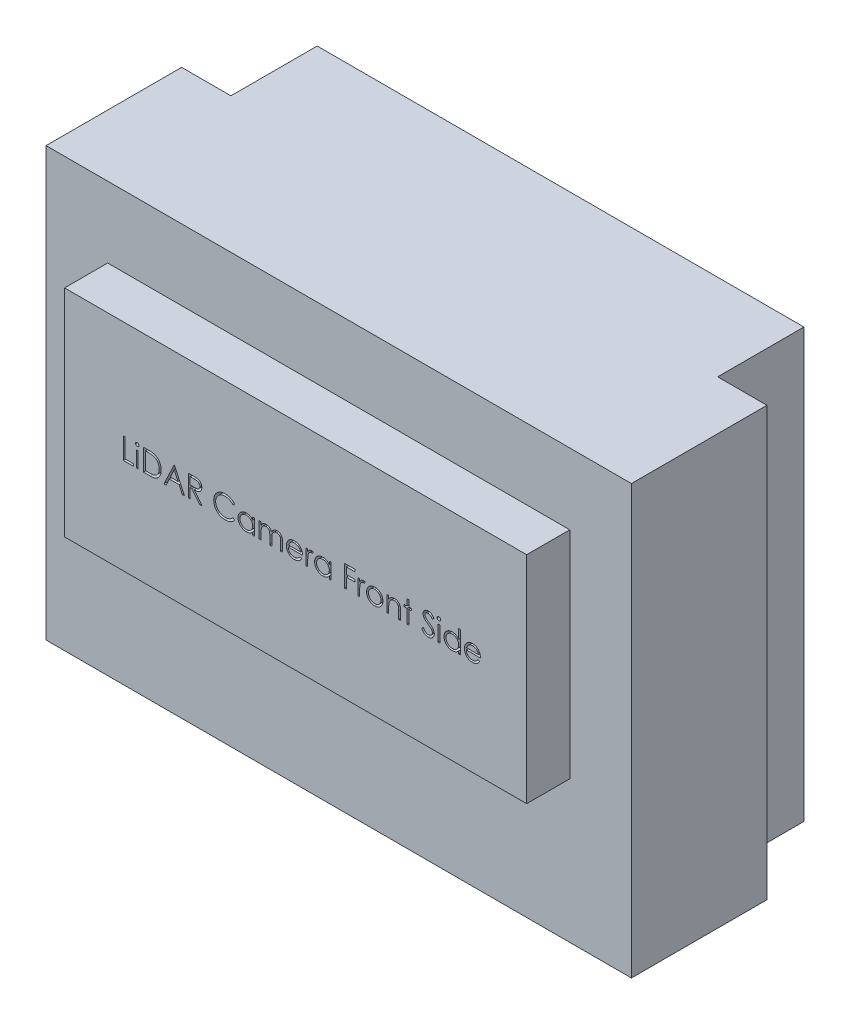
SolidWorks part; units mm, degrees
ref_plane "Front Plane" through (0, 0, 0) normal (0, 0, 1) x (1, 0, 0)
ref_plane "Top Plane" through (0, 0, 0) normal (0, 1, 0) x (1, 0, 0)
ref_plane "Right Plane" through (0, 0, 0) normal (1, 0, 0) x (0, 0, -1)
sketch "Sketch1" plane through (0, 0, 0) normal (0, 0, 1) x (1, 0, 0)
  line L1 (0, 0) -> (95, 0)
  line L2 (0, 0) -> (0, 69.5)
  line L3 (0, 69.5) -> (95, 69.5)
  line L4 (95, 0) -> (95, 69.5)
  dimension "D1" = 95
  dimension "D2" = 69.5
extrude "Body" add sketch "Sketch1" along normal blind 22
sketch "Sketch2" plane through (0, 0, 22) normal (0, 0, 1) x (1, 0, 0)
  line L1 (10, 58) -> (85, 58)
  line L2 (10, 58) -> (10, 23)
  line L3 (10, 23) -> (85, 23)
  line L4 (85, 58) -> (85, 23)
  line L5 (0, 69.5) -> (0, 0) construction
  line L7 (95, 69.5) -> (0, 69.5) construction
  dimension "D1" = 35
  dimension "D2" = 75
  dimension "D3" = 10
  dimension "D4" = 11.5
extrude "Camera Pop Out" add sketch "Sketch2" along normal blind 7 contours L2 L1 L4 L3
sketch "Sketch3" plane through (0, 0, 0) normal (0, 0, -1) x (-1, 0, 0)
  line L0 (-95, 69.5) -> (0, 69.5) construction
  line L1 (-87, 69.5) -> (-8, 69.5)
  line L2 (-87, 69.5) -> (-87, 0)
  line L3 (-87, 0) -> (-8, 0)
  line L4 (-8, 69.5) -> (-8, 0)
  line L5 (-95, 0) -> (-95, 69.5) construction
  dimension "D1" = 79
  dimension "D2" = 69.5
  dimension "D3" = 0
  dimension "D4" = 8
extrude "back side" add sketch "Sketch3" along normal blind 14 contours L2 L1 L4 L3
sketch "Text" plane through (0, 0, 29) normal (0, 0, 1) x (1, 0, 0)
  text T0 "LiDAR Camera Front Side\r\n             " font "Century Gothic" height 3.5
extrude "Cut-Extrude1" cut sketch "Text" against normal blind 2
sketch "Sketch4" plane through (0, 0, 0) normal (0, -1, 0) x (1, 0, 0)
  line L0 (47.5, -14) -> (47.5, 38.4563) construction
  line L2 (95, 11) -> (-7.7272, 11) construction
  point P7 (47.5, 11)
hole_wizard "1/4 (0.25) Diameter Hole1" positions "Sketch4" profile "Sketch5" hole size "1/4" standard "ANSI Inch"
sketch "Sketch5" plane through (47.5, 0, 11) normal (1, 0, 0) x (0, 0, -1)
  line L0 (0, 0) -> (0, 17.3077)
  line L1 (0, 17.3077) -> (3.175, 15.4)
  line L2 (3.175, 15.4) -> (3.175, 0.635)
  line L3 (3.175, 0.635) -> (3.81, 0)
  line L5 (3.81, 0) -> (0, 0)
  line L6 (-3.175, 0.635) -> (-3.81, 0) construction
  line L10 (0, 17.3077) -> (-3.175, 15.4) construction
  line L11 (0, -6.35) -> (0, 107.95) construction
  dimension "Hole Dia." = 6.35
  dimension "Hole Depth" = 15.4
  dimension "Near C'Sink Dia." = 7.62
  dimension "Near C'Sink Angle" = 90
  dimension "Drill Angle" = 118
